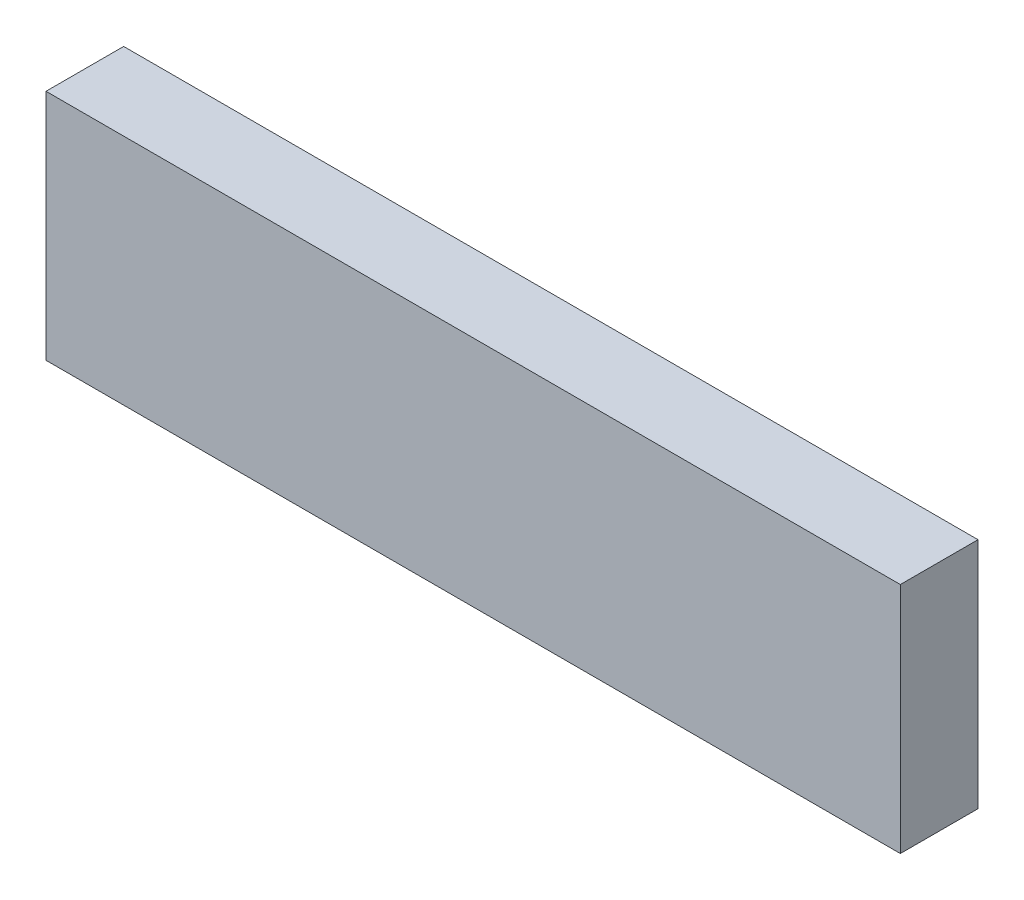
SolidWorks part; units mm, degrees
ref_plane "Front Plane" through (0, 0, 0) normal (0, 0, 1) x (1, 0, 0)
ref_plane "Top Plane" through (0, 0, 0) normal (0, 1, 0) x (1, 0, 0)
ref_plane "Right Plane" through (0, 0, 0) normal (1, 0, 0) x (0, 0, -1)
sketch "Sketch1" plane through (0, 0, 0) normal (0, 0, 1) x (1, 0, 0)
  line L1 (-55, 15) -> (55, 15)
  line L2 (-55, 15) -> (-55, -15)
  line L3 (-55, -15) -> (55, -15)
  line L4 (55, 15) -> (55, -15)
  line L5 (-55, 15) -> (55, -15) construction
  line L6 (-55, -15) -> (55, 15) construction
  point P0 (0, 0)
extrude "Boss-Extrude1" add sketch "Sketch1" against normal blind 10
